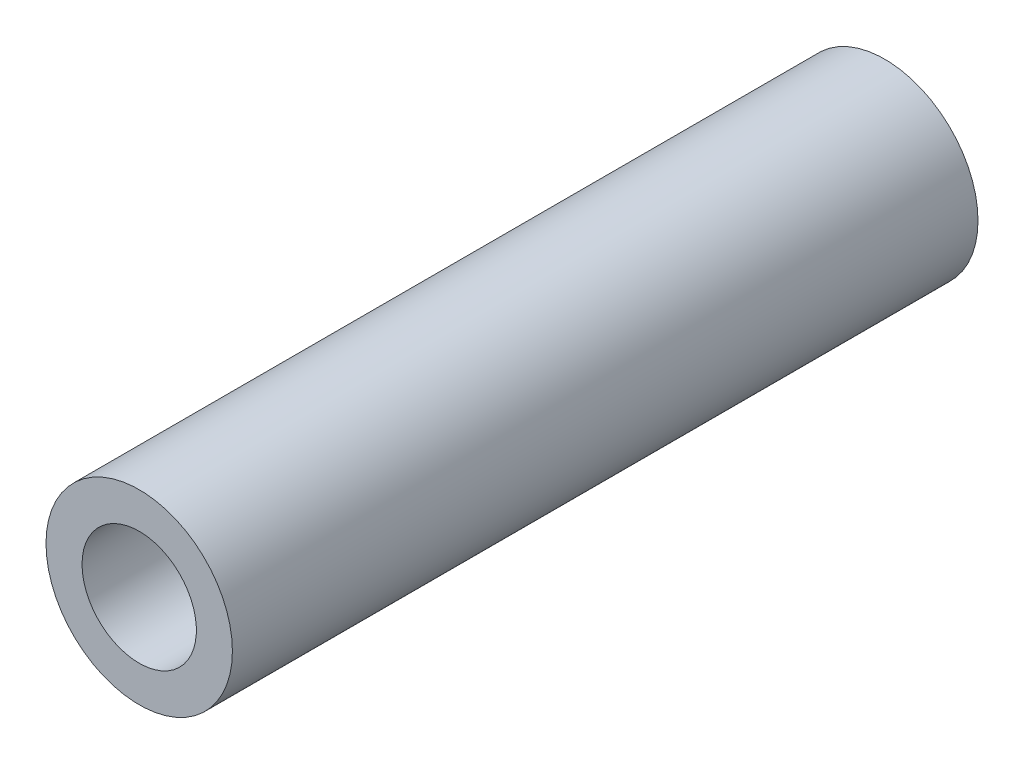
SolidWorks part; units mm, degrees
ref_plane "Front Plane" through (0, 0, 0) normal (0, 0, 1) x (1, 0, 0)
ref_plane "Top Plane" through (0, 0, 0) normal (0, 1, 0) x (1, 0, 0)
ref_plane "Right Plane" through (0, 0, 0) normal (1, 0, 0) x (0, 0, -1)
sketch "Sketch1" plane through (0, 0, 0) normal (0, 0, 1) x (1, 0, 0)
  line L0 (0, 1.4605) -> (0, 2.3813) construction
  line L1 (0, -1.4605) -> (0, -2.3813) construction
  circle A0 centre (0, 0) radius 2.3813
  circle A1 centre (0, 0) radius 1.4605
  dimension "OD" = 4.7625
  dimension "ID" = 2.921
sketch "Sketch2" plane through (0, 0, 0) normal (1, 0, 0) x (0, 0, -1)
  line L0 (-9.525, 1.4605) -> (9.525, 1.4605) construction
  line L1 (-9.525, -1.4605) -> (9.525, -1.4605) construction
  line L2 (-9.525, -2.3813) -> (9.525, -2.3813) construction
  line L3 (-9.525, 2.3813) -> (9.525, 2.3813) construction
  dimension "Length" = 19.05
extrude "Extrude1" add sketch "Sketch1" along normal up to vertex (9.525 mm away) and the other way up to vertex (9.525 mm away) up to point (0, 1.4605, 9.525) other way up to point (0, 1.4605, -9.525)
sketch "Sketch3" plane through (0, 0, 9.525) normal (0, 0, 1) x (1, 0, 0)
  circle A0 centre (0, 0) radius 1.4605 construction
  circle A3 centre (0, 0) radius 1.4605
  point P3 (-1.4605, 0)
